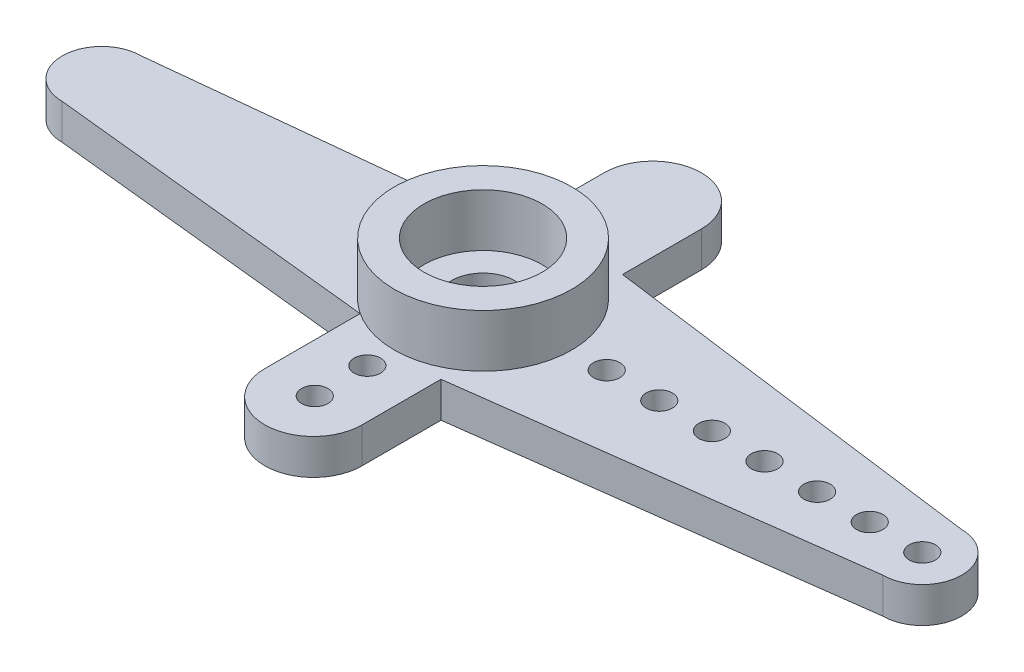
SolidWorks part; units mm, degrees
ref_plane "Piano frontale" through (0, 0, 0) normal (0, 0, 1) x (1, 0, 0)
ref_plane "Piano superiore" through (0, 0, 0) normal (0, 1, 0) x (1, 0, 0)
ref_plane "Piano destro" through (0, 0, 0) normal (1, 0, 0) x (0, 0, -1)
sketch "Schizzo1" plane through (0, 0, 0) normal (0, 1, 0) x (1, 0, 0)
  line L0 (-1.8466, 2.825) -> (-14.5, 1.5)
  line L1 (-1.8466, -2.825) -> (-14.5, -1.5)
  line L2 (-1.8466, 2.825) -> (-1.8466, -2.825)
  line L3 (0, -6.45) -> (0, 6.45) construction
  line L4 (1.85, 3.45) -> (1.85, -3.45)
  line L5 (1.85, -3.45) -> (16.7, -1.5)
  line L6 (1.85, 3.45) -> (16.7, 1.5)
  line L7 (-1.85, -6.45) -> (-1.85, 6.45)
  line L8 (1.85, -6.45) -> (1.85, 6.45)
  circle A0 centre (0, 0) radius 3.375
  arc A1 (-14.5, 1.5) -> (-14.5, -1.5) centre (-14.5, 0) ccw
  arc A2 (16.7, 1.5) -> (16.7, -1.5) centre (16.7, 0) cw
  arc A3 (-1.85, -6.45) -> (1.85, -6.45) centre (0, -6.45) ccw
  arc A4 (1.85, 6.45) -> (-1.85, 6.45) centre (0, 6.45) ccw
  point P8 (-1.8466, 0)
  point P14 (18.2, 0)
  point P18 (1.85, 0)
  point P19 (0, 0)
  point P25 (-16, 0)
  point P31 (0, 8.3)
  point P32 (0, -8.3)
  dimension "D1" = 6.75
  dimension "D3" = 1.5
  dimension "D7" = 1.5
  dimension "D2" = 5.65
  dimension "D4" = 3
  dimension "D5" = 16
  dimension "D6" = 6.9
  dimension "D8" = 3
  dimension "D9" = 34.2
  dimension "D10" = 3.7
  dimension "D11" = 16.6
extrude "Estrusione-Estrusione1" add sketch "Schizzo1" along normal blind 1.35
sketch "Schizzo2" plane through (0, 1.35, 0) normal (0, 1, 0) x (1, 0, 0)
  circle A0 centre (0, 0) radius 3.375
  dimension "D1" = 6.75
extrude "Estrusione-Estrusione2" add sketch "Schizzo2" along normal blind 2
sketch "Schizzo3" plane through (0, 3.35, 0) normal (0, 1, 0) x (1, 0, 0)
  circle A0 centre (0, 0) radius 2.25
  dimension "D1" = 4.5
extrude "Taglio-Estrusione1" cut sketch "Schizzo3" against normal blind 2
sketch "Schizzo4" plane through (0, 1.35, 0) normal (0, 1, 0) x (1, 0, 0)
  circle A0 centre (0, 0) radius 1.2
  dimension "D1" = 2.4
extrude "Taglio-Estrusione2" cut sketch "Schizzo4" against normal through all
sketch "Schizzo5" plane through (0, 0, 0) normal (0, -1, 0) x (1, 0, 0)
  circle A5 centre (8.7, 0) radius 0.5
  circle A6 centre (10.7, 0) radius 0.5
  circle A7 centre (12.7, 0) radius 0.5
  circle A8 centre (14.7, 0) radius 0.5
  circle A9 centre (16.7, 0) radius 0.5
  circle A10 centre (6.7, 0) radius 0.5
  circle A11 centre (4.7, 0) radius 0.5
  circle A12 centre (0, 4.4) radius 0.5
  circle A13 centre (0, 6.4) radius 0.5
  dimension "D1" = 1
  dimension "D2" = 1
  dimension "D3" = 1
  dimension "D4" = 1
  dimension "D5" = 1
  dimension "D6" = 1
  dimension "D7" = 1
  dimension "D8" = 2
  dimension "D9" = 2
  dimension "D10" = 2
  dimension "D11" = 2
  dimension "D12" = 2
  dimension "D13" = 2
  dimension "D15" = 1
  dimension "D16" = 1
  dimension "D14" = 4.7
  dimension "D17" = 2
  dimension "D18" = 4.4
extrude "Taglio-Estrusione3" cut sketch "Schizzo5" against normal through all
